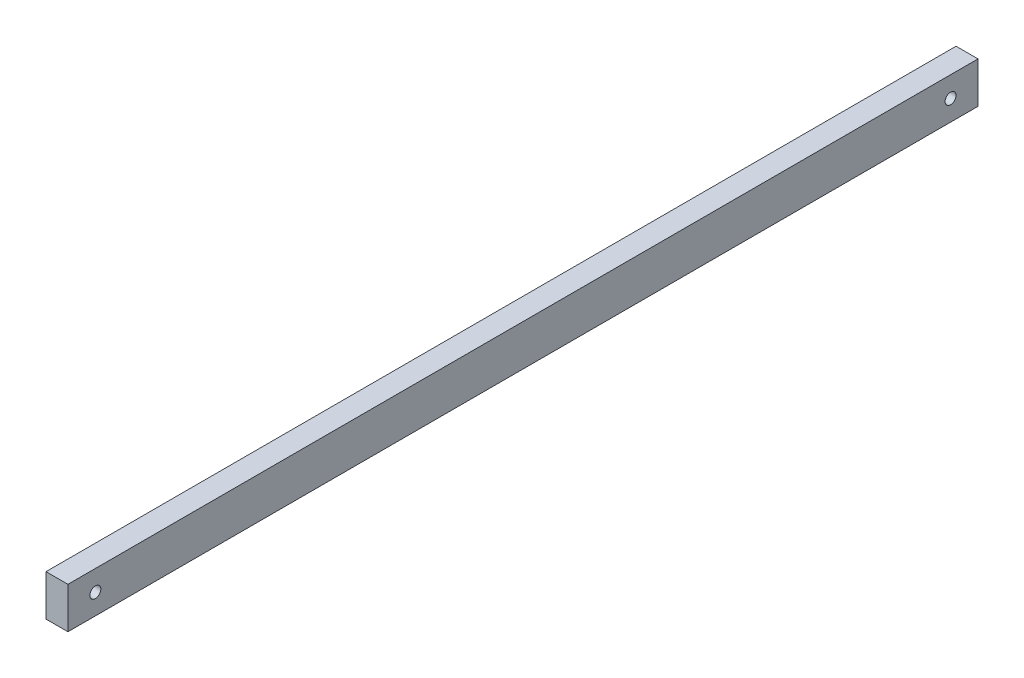
SolidWorks part; units mm, degrees
ref_plane "Front Plane" through (0, 0, 0) normal (0, 0, 1) x (1, 0, 0)
ref_plane "Top Plane" through (0, 0, 0) normal (0, 1, 0) x (1, 0, 0)
ref_plane "Right Plane" through (0, 0, 0) normal (1, 0, 0) x (0, 0, -1)
sketch "Sketch1" plane through (0, 0, 0) normal (0, 0, 1) x (1, 0, 0)
  line L1 (-4, -7.5) -> (4, -7.5)
  line L2 (-4, -7.5) -> (-4, 7.5)
  line L3 (-4, 7.5) -> (4, 7.5)
  line L4 (4, -7.5) -> (4, 7.5)
  line L5 (-4, -7.5) -> (4, 7.5) construction
  line L6 (-4, 7.5) -> (4, -7.5) construction
  point P0 (0, 0)
  dimension "D1" = 8
  dimension "D2" = 15
extrude "Boss-Extrude1" add sketch "Sketch1" along normal blind 332
sketch "Sketch2" plane through (-4, 0, 0) normal (-1, 0, 0) x (0, 0, 1)
  line L0 (332, 7.5) -> (332, -7.5) construction
  line L1 (0, 7.5) -> (0, -7.5) construction
  circle A0 centre (10, 0) radius 2
  circle A1 centre (322, 0) radius 2
  dimension "D1" = 10
  dimension "D3" = 4
  dimension "D2" = 10
extrude "Cut-Extrude1" cut sketch "Sketch2" against normal up to next
